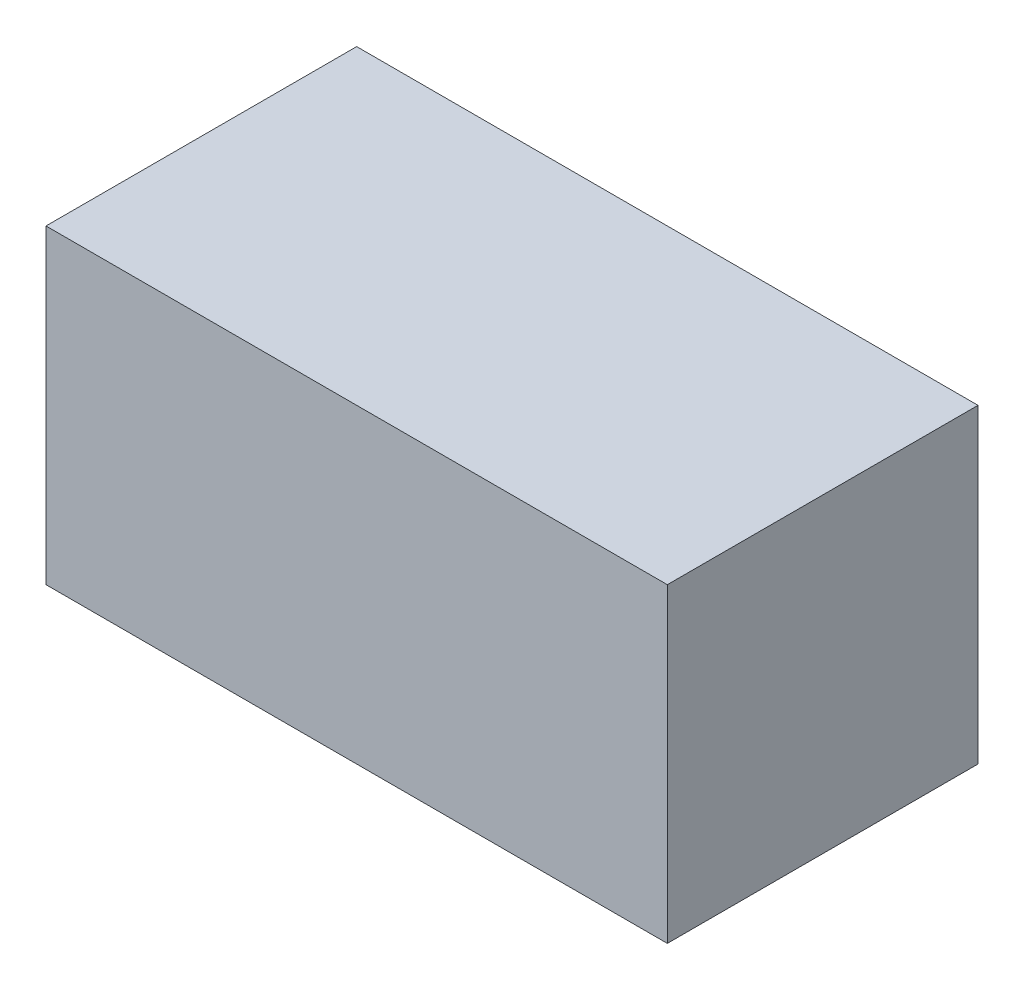
SolidWorks part; units mm, degrees
ref_plane "Front Plane" through (0, 0, 0) normal (0, 0, 1) x (1, 0, 0)
ref_plane "Top Plane" through (0, 0, 0) normal (0, 1, 0) x (1, 0, 0)
ref_plane "Right Plane" through (0, 0, 0) normal (1, 0, 0) x (0, 0, -1)
sketch "Sketch1" plane through (0, 0, 0) normal (0, 1, 0) x (1, 0, 0)
  line L1 (-25, -12.5) -> (25, -12.5)
  line L2 (-25, -12.5) -> (-25, 12.5)
  line L3 (-25, 12.5) -> (25, 12.5)
  line L4 (25, -12.5) -> (25, 12.5)
  line L5 (-25, -12.5) -> (25, 12.5) construction
  line L6 (-25, 12.5) -> (25, -12.5) construction
  point P0 (0, 0)
  dimension "D1" = 25
  dimension "D2" = 50
extrude "Boss-Extrude1" add sketch "Sketch1" along normal blind 25
